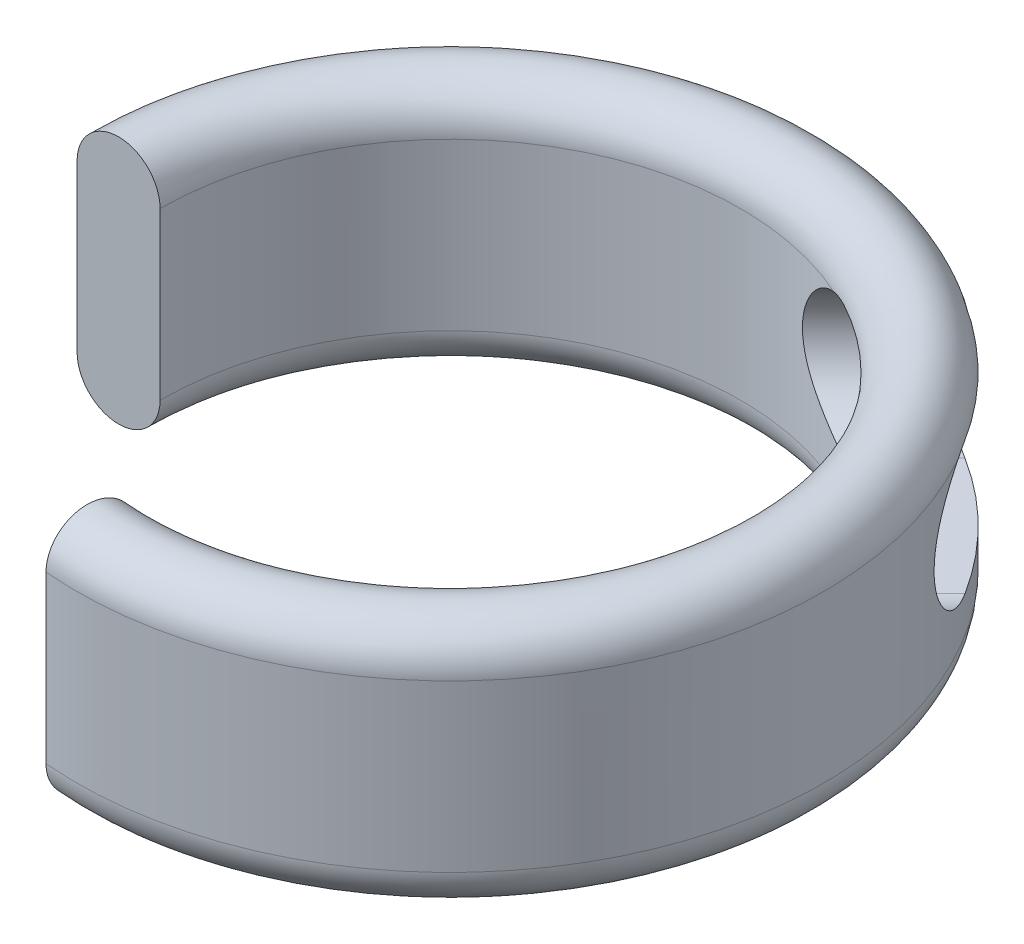
SolidWorks part; units mm, degrees
ref_plane "Front Plane" through (0, 0, 0) normal (0, 0, 1) x (1, 0, 0)
ref_plane "Top Plane" through (0, 0, 0) normal (0, 1, 0) x (1, 0, 0)
ref_plane "Right Plane" through (0, 0, 0) normal (1, 0, 0) x (0, 0, -1)
sketch "Sketch1" plane through (0, 0, 0) normal (0, 0, 1) x (1, 0, 0)
  line L0 (0, 8.7573) -> (0, -12.1558) construction
  line L3 (-20, -7.7886) -> (-20, 17.7886) construction
  line L4 (-22.5, -5) -> (-22.5, 5)
  line L5 (-17.5, -5) -> (-17.5, 5)
  arc A2 (-22.5, 5) -> (-17.5, 5) centre (-20, 5) cw
  arc A3 (-17.5, -5) -> (-22.5, -5) centre (-20, -5) cw
  point P3 (-17.5, 0)
  dimension "D6" = 10
  dimension "D4" = 20
  dimension "D5" = 2.5
revolve "Revolve1" add sketch "Sketch1" angle 275 about L0
ref_plane "Plane1" through (0, 0, 0) normal (0.7071, 0, -0.7071) x (-0.7071, 0, -0.7071)
ref_plane "Plane2" through (21.2132, 0, -21.2132) normal (0.7071, 0, -0.7071) x (-0.7071, 0, -0.7071)
sketch "Sketch2" plane through (21.2132, 0, -21.2132) normal (0.7071, 0, -0.7071) x (-0.7071, 0, -0.7071)
  line L0 (37.0183, 1.1834) -> (-37.5123, 1.1834) construction
  line L1 (0, 30.0056) -> (0, -19.6388) construction
  line L2 (0, -7.8166) -> (-42.6954, -7.8166) construction
  line L3 (-5, 5.1834) -> (5, 5.1834)
  line L4 (-5, -2.8166) -> (5, -2.8166)
  arc A0 (-5, -2.8166) -> (-5, 5.1834) centre (-5, 1.1834) cw
  arc A1 (5, 5.1834) -> (5, -2.8166) centre (5, 1.1834) cw
  point P9 (0, 5.1834)
  dimension "D1" = 9
  dimension "D2" = 4
  dimension "D3" = 10
extrude "Cut-Extrude1" cut sketch "Sketch2" against normal up to next
